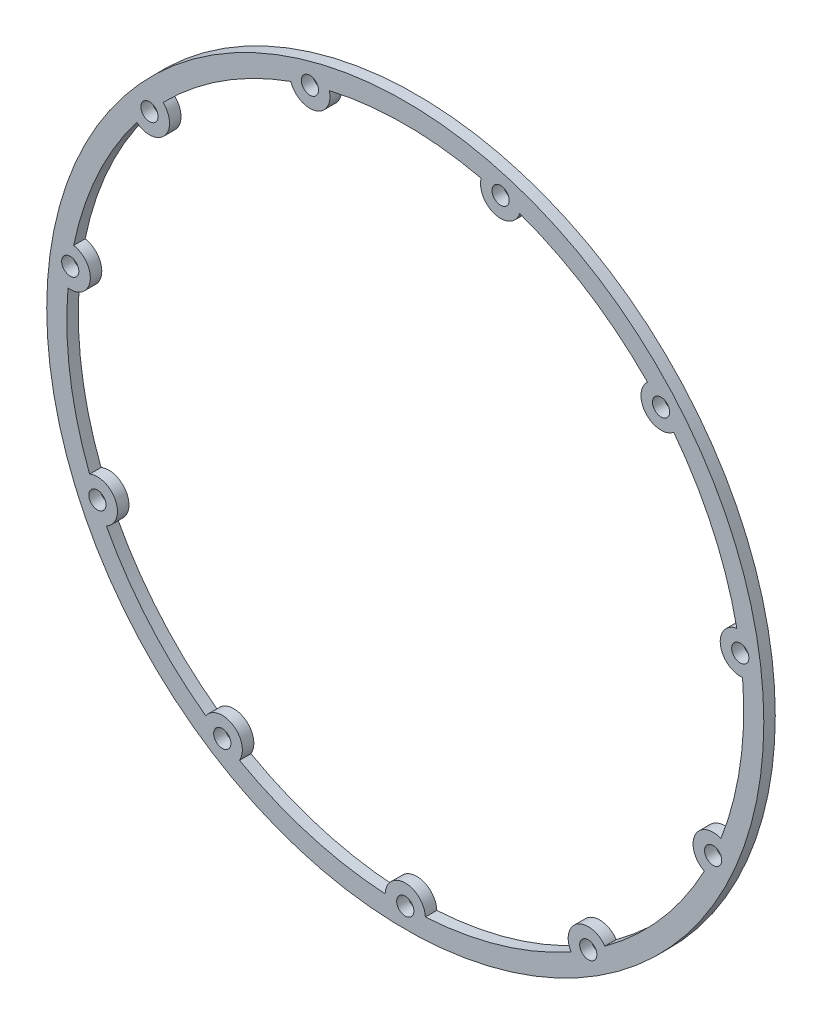
SolidWorks part; units mm, degrees
ref_plane "前视基准面" through (0, 0, 0) normal (0, 0, 1) x (1, 0, 0)
ref_plane "上视基准面" through (0, 0, 0) normal (0, 1, 0) x (1, 0, 0)
ref_plane "右视基准面" through (0, 0, 0) normal (1, 0, 0) x (0, 0, -1)
sketch "草图1" plane through (0, 0, 0) normal (0, 0, 1) x (1, 0, 0)
  line L0 (0, -59) -> (0, 0) construction
  line L1 (0, 0) -> (21.3581, 0) construction
  circle A1 centre (0, 0) radius 62.5
  circle A2 centre (0, 0) radius 59 construction
  circle A3 centre (0, -59) radius 1.5
  circle A4 centre (0, -59) radius 3.5 construction
  arc A5 (3.4985, -58.8962) -> (-3.4985, -58.8962) centre (0, -59) ccw
  circle A6 centre (-31.8978, -49.634) radius 1.5
  circle A7 centre (-53.6683, -24.5095) radius 1.5
  circle A8 centre (-58.3995, 8.3966) radius 1.5
  circle A9 centre (-44.5892, 38.6368) radius 1.5
  circle A10 centre (-16.6222, 56.6101) radius 1.5
  circle A11 centre (16.6222, 56.6101) radius 1.5
  circle A12 centre (44.5892, 38.6368) radius 1.5
  circle A13 centre (58.3995, 8.3966) radius 1.5
  circle A14 centre (53.6683, -24.5095) radius 1.5
  circle A15 centre (31.8978, -49.634) radius 1.5
  circle A16 centre (31.8978, -49.634) radius 3.5 construction
  arc A17 (28.8986, -51.438) -> (3.4985, -58.8962) centre (0, 0) cw
  arc A18 (-3.4985, -58.8962) -> (-28.8986, -51.438) centre (0, 0) cw
  arc A19 (-28.8986, -51.438) -> (-34.7848, -47.6552) centre (-31.8978, -49.634) ccw
  arc A20 (-34.7848, -47.6552) -> (-52.1205, -27.6487) centre (0, 0) cw
  arc A21 (-52.1205, -27.6487) -> (-55.0272, -21.284) centre (-53.6683, -24.5095) ccw
  arc A22 (-55.0272, -21.284) -> (-58.7946, 4.919) centre (0, 0) cw
  arc A23 (-58.7946, 4.919) -> (-57.7988, 11.8447) centre (-58.3995, 8.3966) ccw
  arc A24 (-57.7988, 11.8447) -> (-46.8018, 35.9248) centre (0, 0) cw
  arc A25 (-46.8018, 35.9248) -> (-42.2198, 41.2128) centre (-44.5892, 38.6368) ccw
  arc A26 (-42.2198, 41.2128) -> (-19.9497, 55.5248) centre (0, 0) cw
  arc A27 (-19.9497, 55.5248) -> (-13.2362, 57.4961) centre (-16.6222, 56.6101) ccw
  arc A28 (-13.2362, 57.4961) -> (13.2362, 57.4961) centre (0, 0) cw
  arc A29 (13.2362, 57.4961) -> (19.9497, 55.5248) centre (16.6222, 56.6101) ccw
  arc A30 (19.9497, 55.5248) -> (42.2198, 41.2128) centre (0, 0) cw
  arc A31 (42.2198, 41.2128) -> (46.8018, 35.9248) centre (44.5892, 38.6368) ccw
  arc A32 (46.8018, 35.9248) -> (57.7988, 11.8447) centre (0, 0) cw
  arc A33 (57.7988, 11.8447) -> (58.7946, 4.919) centre (58.3995, 8.3966) ccw
  arc A34 (58.7946, 4.919) -> (55.0272, -21.284) centre (0, 0) cw
  arc A35 (55.0272, -21.284) -> (52.1205, -27.6487) centre (53.6683, -24.5095) ccw
  arc A36 (52.1205, -27.6487) -> (34.7848, -47.6552) centre (0, 0) cw
  arc A37 (34.7848, -47.6552) -> (28.8986, -51.438) centre (31.8978, -49.634) ccw
  point P7 (0, 0)
  dimension "D1" = 11
  dimension "D2" = 125
  dimension "D3" = 118
  dimension "D4" = 3
  dimension "D5" = 11
extrude "凸台-拉伸1" add sketch "草图1" along normal blind 2 contours A4
